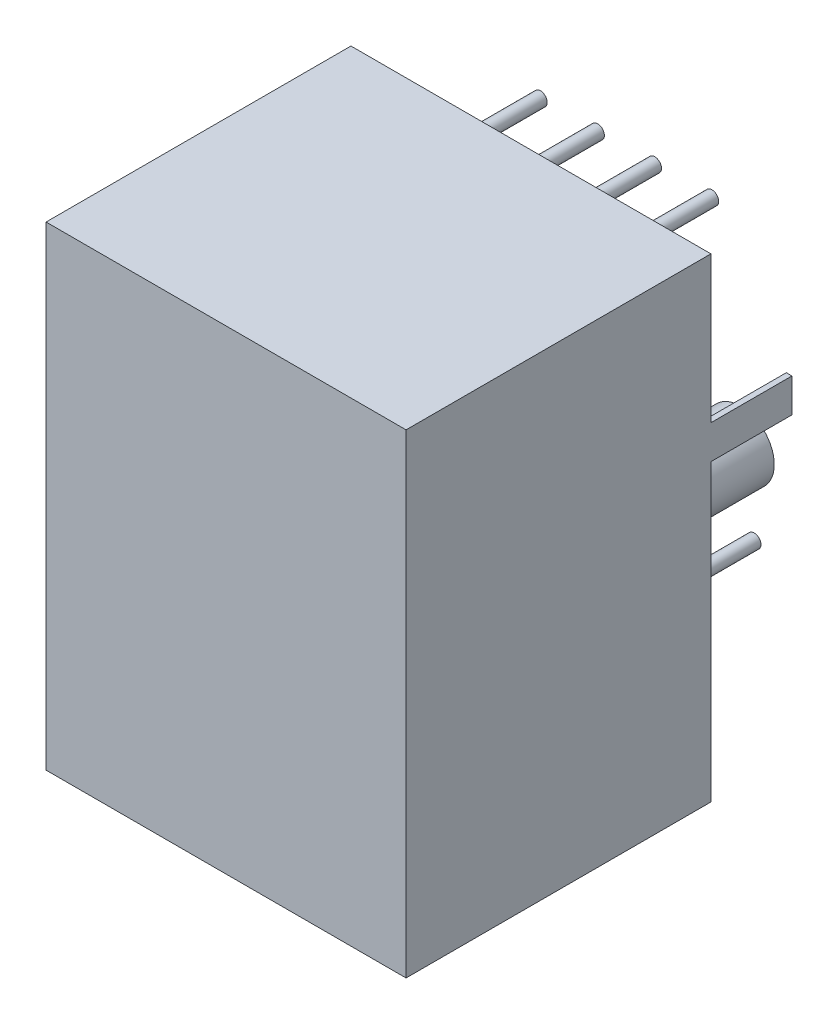
SolidWorks part; units mm, degrees
other "Детальный элемент1"
ref_plane "Спереди" through (0, 0, 0) normal (0, 0, 1) x (1, 0, 0)
ref_plane "Сверху" through (0, 0, 0) normal (0, 1, 0) x (1, 0, 0)
ref_plane "Справа" through (0, 0, 0) normal (1, 0, 0) x (0, 0, -1)
sketch "Эскиз1" plane through (0, 0, 0) normal (0, 0, 1) x (1, 0, 0)
  line L0 (-8, 0) -> (0, 0)
  line L2 (-8, 0) -> (-8, 21.1)
  line L3 (-8, 21.1) -> (0, 21.1)
  line L4 (0, 0) -> (0, 21.1)
  dimension "D1" = 8
  dimension "D2" = 21.1
extrude "Бобышка-Вытянуть1" add sketch "Эскиз1" along normal blind 13.55
sketch "Эскиз2" plane through (0, 0, 0) normal (0, 0, -1) x (-1, 0, 0)
  line L0 (0, 0) -> (0, 21.1) construction
  line L1 (8, 0) -> (0, 0) construction
  line L4 (8, 13.1) -> (7.75, 13.1)
  line L5 (8, 13.1) -> (8, 14.6)
  line L6 (8, 14.6) -> (7.75, 14.6)
  line L7 (7.75, 13.1) -> (7.75, 14.6)
  line L8 (8, 13.1) -> (7.75, 14.6) construction
  line L9 (8, 14.6) -> (7.75, 13.1) construction
  line L10 (8, 21.1) -> (8, 0) construction
  circle A0 centre (5.715, 10.8) radius 1.5
  point P2 (7.875, 13.85)
  dimension "D7" = 3
  dimension "D1" = 5.715
  dimension "D2" = 7.875
  dimension "D3" = 10.8
  dimension "D4" = 3.05
  dimension "D5" = 1.5
extrude "Бобышка-Вытянуть2" add sketch "Эскиз2" along normal blind 3.6
sketch "Эскиз3" plane through (0, 0, 0) normal (0, -1, 0) x (1, 0, 0)
  line L0 (0, 1) -> (-2, 1)
  line L1 (0, 13.55) -> (0, 0) construction
  line L2 (-2, 1) -> (-2, 2.3)
  line L3 (-2, 2.3) -> (-3.2, 2.3)
  line L4 (-3.2, 2.3) -> (-3.2, 4)
  line L5 (-3.2, 4) -> (-6, 4)
  line L6 (-6, 4) -> (-6, 11.05)
  line L7 (-6, 11.05) -> (0, 11.05)
  line L8 (0, 11.05) -> (0, 1)
  line L9 (-8, 0) -> (0, 0) construction
  line L10 (-8, 13.55) -> (-8, 0) construction
  line L11 (-8, 13.55) -> (0, 13.55) construction
  dimension "D1" = 1
  dimension "D2" = 2.3
  dimension "D3" = 4
  dimension "D4" = 4.8
  dimension "D5" = 6
  dimension "D6" = 2
  dimension "D7" = 2.5
extrude "Вырез-Вытянуть1" cut sketch "Эскиз3" against normal blind 12
sketch "Эскиз4" plane through (0, 0, 0) normal (0, -1, 0) x (1, 0, 0)
  line L0 (-8, 13.55) -> (-8, 0) construction
  line L1 (-7, 1) -> (-3.9, 1)
  line L2 (-7, 1) -> (-7, 2.8)
  line L3 (-7, 2.8) -> (-3.9, 2.8)
  line L4 (-3.9, 1) -> (-3.9, 2.8)
  line L5 (-7, 1) -> (-3.9, 2.8) construction
  line L6 (-7, 2.8) -> (-3.9, 1) construction
  line L7 (-8, 0) -> (0, 0) construction
  point P0 (-5.45, 1.9)
  point P5 (-5.7907, 2.8097)
  point P6 (-5.2999, 2.5954)
  dimension "D1" = 3.1
  dimension "D2" = 1.8
  dimension "D3" = 1
  dimension "D4" = 1
extrude "Вырез-Вытянуть2" cut sketch "Эскиз4" against normal blind 0.01
mirror "Зеркальное отражение1" about plane through (0, 0, 13.55) normal (-1, 0, 0) of bodies 111 108
sketch "Эскиз5" plane through (0, 0, 0) normal (0, 0, -1) x (-1, 0, 0)
  circle A0 centre (-6.325, 7.42) radius 0.3
  circle A1 centre (-3.785, 5.9) radius 0.3
  circle A2 centre (3.785, 7.42) radius 0.3
  circle A3 centre (6.325, 5.9) radius 0.3
  circle A4 centre (-4.445, 19.69) radius 0.3
  circle A5 centre (-1.905, 19.69) radius 0.3
  circle A6 centre (0.635, 19.69) radius 0.3
  circle A7 centre (3.175, 19.69) radius 0.3
  circle A8 centre (-3.175, 17.15) radius 0.3
  circle A9 centre (-0.635, 17.15) radius 0.3
  circle A10 centre (1.905, 17.15) radius 0.3
  circle A11 centre (4.445, 17.15) radius 0.3
  circle A13 centre (-5.715, 10.8) radius 1.5 construction
  point P24 (0, 0)
  point P25 (0, 0)
  point P26 (0, 0)
  point P27 (0, 0)
  point P30 (0, 0)
  point P31 (-6.2059, 7.7561)
  point P33 (-4.5749, 19.69)
  dimension "D7" = 0.6
  dimension "D16" = 8.89
  dimension "D1" = 4.9
  dimension "D2" = 1.52
  dimension "D3" = 7.57
  dimension "D4" = 3.785
  dimension "D5" = 12.65
  dimension "D6" = 6.325
  dimension "D8" = 1.27
  dimension "D9" = 1.27
  dimension "D10" = 1.27
  dimension "D11" = 1.27
  dimension "D12" = 1.27
  dimension "D13" = 1.27
  dimension "D14" = 1.27
  dimension "D15" = 2.54
  dimension "D17" = 4.445
extrude "Бобышка-Вытянуть3" add sketch "Эскиз5" along normal blind 3.6
